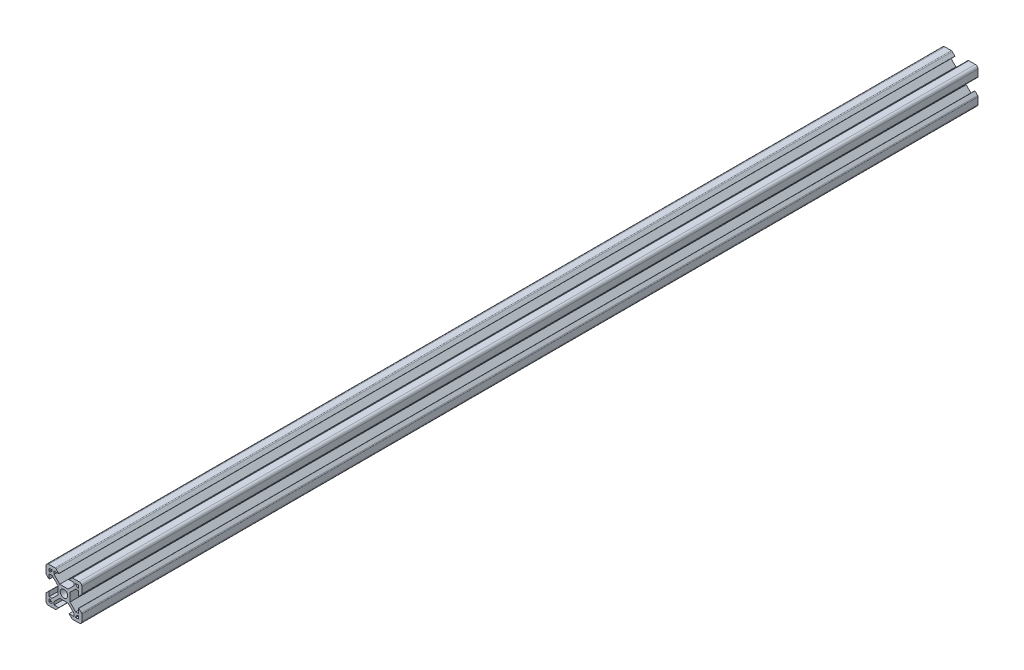
SolidWorks part; units mm, degrees
ref_plane "Front Plane" through (0, 0, 0) normal (0, 0, 1) x (1, 0, 0)
ref_plane "Top Plane" through (0, 0, 0) normal (0, 1, 0) x (1, 0, 0)
ref_plane "Right Plane" through (0, 0, 0) normal (1, 0, 0) x (0, 0, -1)
sketch "Sketch2" plane through (0, 0, 0) normal (0, 0, 1) x (1, 0, 0)
  line L0 (-8.2, 2.89) -> (-8.2, 5.5)
  line L1 (-2.1, 0) -> (-10, 0) construction
  line L2 (0, 2.1) -> (0, 10) construction
  line L3 (-4.9072, 10) -> (-8.5, 10)
  line L4 (-10, 4.9072) -> (-10, 8.5)
  line L5 (-2.1, 0) -> (-3.4, 0) construction
  line L6 (0, 2.1) -> (0, 3.4) construction
  line L7 (0, 3.4) -> (-2.3393, 3.4)
  line L8 (-3.4, 0) -> (-3.4, 2.3393)
  line L9 (-2.89, 8.2) -> (-5.5, 8.2)
  line L10 (-6.57, 8.2) -> (-6.57, 7.66)
  line L11 (-8.2, 6.57) -> (-7.66, 6.57)
  line L12 (-5.5, 8.2) -> (-5.5, 6.5607)
  line L13 (-6.5607, 5.5) -> (-8.2, 5.5)
  line L14 (-8.2, 8.2) -> (-1.4849, 1.4849) construction
  line L15 (-6.5607, 5.5) -> (-3.4, 2.3393)
  line L16 (-5.5, 6.5607) -> (-2.3393, 3.4)
  line L17 (-7.66, 6.57) -> (-6.57, 7.66)
  line L18 (-8.7303, 7.6697) -> (-0.5303, -0.5303) construction
  line L19 (-7.6697, 8.7303) -> (0.5303, 0.5303) construction
  line L20 (-8.2, 8.2) -> (0, 0) construction
  line L21 (-8.2, 6.57) -> (-8.2, 8.2)
  line L22 (-8.2, 0) -> (-8.2, 8.2) construction
  line L23 (-6.57, 8.2) -> (-8.2, 8.2)
  line L24 (0, 8.2) -> (-8.2, 8.2) construction
  line L25 (-10, 0) -> (-10, 10) construction
  line L26 (0, 10) -> (-10, 10) construction
  line L27 (-2.89, 8.31) -> (-2.89, 8.2)
  line L29 (-8.31, 2.89) -> (-8.2, 2.89)
  line L30 (-4.3486, 9.7686) -> (-2.89, 8.31)
  line L31 (-8.31, 2.89) -> (-9.7686, 4.3486)
  arc A0 (0, 2.1) -> (-2.1, 0) centre (0, 0) ccw
  arc A1 (-10, 8.5) -> (-8.5, 10) centre (-8.5, 8.5) cw
  arc A2 (-9.7686, 4.3486) -> (-10, 4.9072) centre (-9.21, 4.9072) cw
  arc A3 (-4.3486, 9.7686) -> (-4.9072, 10) centre (-4.9072, 9.21) ccw
  point P29 (-10, 10)
  point P39 (-10, 4.58)
  point P42 (-4.58, 10)
  dimension "D3" = 2.1
  dimension "D15" = 1.5
  dimension "D22" = 0.79
  dimension "D1" = 10
  dimension "D2" = 10
  dimension "D4" = 1.8
  dimension "D5" = 3.43
  dimension "D6" = 3.43
  dimension "D7" = 0.54
  dimension "D8" = 0.54
  dimension "D9" = 1.07
  dimension "D10" = 1.07
  dimension "D11" = 3.4
  dimension "D12" = 3.4
  dimension "D16" = 7.11
  dimension "D17" = 0.11
  dimension "D18" = 1.69
  dimension "D19" = 0.11
  dimension "D20" = 7.11
  dimension "D21" = 1.69
  dimension "D13" = 0.75
  dimension "D14" = 0.75
sketch "Sketch6" plane through (0, 0, 0) normal (0, 0, 1) x (1, 0, 0)
  line L0 (-3.4, 0) -> (-3.4, 2.3393) construction
  line L1 (-6.5607, 5.5) -> (-3.4, 2.3393) construction
  line L2 (-6.5607, 5.5) -> (-8.2, 5.5) construction
  line L3 (-8.2, 2.89) -> (-8.2, 5.5) construction
  line L4 (-8.31, 2.89) -> (-8.2, 2.89) construction
  line L5 (-7.66, 6.57) -> (-6.57, 7.66)
  line L6 (-6.57, 7.66) -> (-6.57, 8.2)
  line L7 (-6.57, 8.2) -> (-8.2, 8.2)
  line L8 (-8.2, 8.2) -> (-8.2, 6.57)
  line L9 (-8.2, 6.57) -> (-7.66, 6.57)
  line L10 (-7.66, 6.57) -> (-6.57, 7.66)
  line L11 (-6.57, 7.66) -> (-6.57, 8.2)
  line L12 (-6.57, 8.2) -> (-8.2, 8.2)
  line L13 (-8.2, 8.2) -> (-8.2, 6.57)
  line L14 (-8.2, 6.57) -> (-7.66, 6.57)
  line L15 (-8.31, 2.89) -> (-9.7686, 4.3486) construction
  line L16 (-10, 4.9072) -> (-10, 8.5) construction
  line L17 (-4.9072, 10) -> (-8.5, 10) construction
  line L18 (-4.3486, 9.7686) -> (-2.89, 8.31) construction
  line L19 (-2.89, 8.31) -> (-2.89, 8.2) construction
  line L20 (-2.89, 8.2) -> (-5.5, 8.2) construction
  line L21 (-5.5, 8.2) -> (-5.5, 6.5607) construction
  line L22 (-5.5, 6.5607) -> (-2.3393, 3.4) construction
  line L23 (0, 3.4) -> (-2.3393, 3.4) construction
  line L24 (-3.4, -2.3393) -> (-3.4, 2.3393)
  line L25 (-6.5607, 5.5) -> (-3.4, 2.3393)
  line L26 (-6.5607, 5.5) -> (-8.2, 5.5)
  line L27 (-8.2, 2.89) -> (-8.2, 5.5)
  line L28 (-8.31, 2.89) -> (-8.2, 2.89)
  line L29 (-8.31, 2.89) -> (-9.7686, 4.3486)
  line L30 (-10, 4.9072) -> (-10, 8.5)
  line L31 (-4.9072, 10) -> (-8.5, 10)
  line L32 (-4.3486, 9.7686) -> (-2.89, 8.31)
  line L33 (-2.89, 8.31) -> (-2.89, 8.2)
  line L34 (-2.89, 8.2) -> (-5.5, 8.2)
  line L35 (-5.5, 8.2) -> (-5.5, 6.5607)
  line L36 (-5.5, 6.5607) -> (-2.3393, 3.4)
  line L37 (2.3393, 3.4) -> (-2.3393, 3.4)
  line L38 (0, 2.1) -> (0, 10) construction
  line L39 (-2.1, 0) -> (-10, 0) construction
  line L40 (0, 2.1) -> (0, 10) construction
  line L41 (-2.1, 0) -> (-10, 0) construction
  line L42 (2.1, 0) -> (10, 0) construction
  line L43 (5.5, 6.5607) -> (2.3393, 3.4)
  line L44 (5.5, 8.2) -> (5.5, 6.5607)
  line L45 (2.89, 8.2) -> (5.5, 8.2)
  line L46 (2.89, 8.31) -> (2.89, 8.2)
  line L47 (4.3486, 9.7686) -> (2.89, 8.31)
  line L48 (4.9072, 10) -> (8.5, 10)
  line L49 (10, 4.9072) -> (10, 8.5)
  line L50 (8.31, 2.89) -> (9.7686, 4.3486)
  line L51 (8.31, 2.89) -> (8.2, 2.89)
  line L52 (8.2, 2.89) -> (8.2, 5.5)
  line L53 (6.5607, 5.5) -> (8.2, 5.5)
  line L54 (6.5607, 5.5) -> (3.4, 2.3393)
  line L55 (3.4, -2.3393) -> (3.4, 2.3393)
  line L56 (8.2, 6.57) -> (7.66, 6.57)
  line L57 (8.2, 8.2) -> (8.2, 6.57)
  line L58 (6.57, 8.2) -> (8.2, 8.2)
  line L59 (6.57, 7.66) -> (6.57, 8.2)
  line L60 (7.66, 6.57) -> (6.57, 7.66)
  line L61 (0, -2.1) -> (0, -10) construction
  line L62 (7.66, -6.57) -> (6.57, -7.66)
  line L63 (6.57, -7.66) -> (6.57, -8.2)
  line L64 (6.57, -8.2) -> (8.2, -8.2)
  line L65 (8.2, -8.2) -> (8.2, -6.57)
  line L66 (8.2, -6.57) -> (7.66, -6.57)
  line L67 (6.5607, -5.5) -> (3.4, -2.3393)
  line L68 (6.5607, -5.5) -> (8.2, -5.5)
  line L69 (8.2, -2.89) -> (8.2, -5.5)
  line L70 (8.31, -2.89) -> (8.2, -2.89)
  line L71 (8.31, -2.89) -> (9.7686, -4.3486)
  line L72 (10, -4.9072) -> (10, -8.5)
  line L73 (4.9072, -10) -> (8.5, -10)
  line L74 (4.3486, -9.7686) -> (2.89, -8.31)
  line L75 (2.89, -8.31) -> (2.89, -8.2)
  line L76 (2.89, -8.2) -> (5.5, -8.2)
  line L77 (5.5, -8.2) -> (5.5, -6.5607)
  line L78 (5.5, -6.5607) -> (2.3393, -3.4)
  line L79 (2.3393, -3.4) -> (-2.3393, -3.4)
  line L80 (-5.5, -6.5607) -> (-2.3393, -3.4)
  line L81 (-5.5, -8.2) -> (-5.5, -6.5607)
  line L82 (-2.89, -8.2) -> (-5.5, -8.2)
  line L83 (-2.89, -8.31) -> (-2.89, -8.2)
  line L84 (-4.3486, -9.7686) -> (-2.89, -8.31)
  line L85 (-4.9072, -10) -> (-8.5, -10)
  line L86 (-10, -4.9072) -> (-10, -8.5)
  line L87 (-8.31, -2.89) -> (-9.7686, -4.3486)
  line L88 (-8.31, -2.89) -> (-8.2, -2.89)
  line L89 (-8.2, -2.89) -> (-8.2, -5.5)
  line L90 (-6.5607, -5.5) -> (-8.2, -5.5)
  line L91 (-6.5607, -5.5) -> (-3.4, -2.3393)
  line L92 (-8.2, -6.57) -> (-7.66, -6.57)
  line L93 (-8.2, -8.2) -> (-8.2, -6.57)
  line L94 (-6.57, -8.2) -> (-8.2, -8.2)
  line L95 (-6.57, -7.66) -> (-6.57, -8.2)
  line L96 (-7.66, -6.57) -> (-6.57, -7.66)
  arc A0 (0, 2.1) -> (-2.1, 0) centre (0, 0) ccw construction
  arc A1 (-10, 4.9072) -> (-9.7686, 4.3486) centre (-9.21, 4.9072) ccw construction
  arc A2 (-8.5, 10) -> (-10, 8.5) centre (-8.5, 8.5) ccw construction
  arc A3 (-4.3486, 9.7686) -> (-4.9072, 10) centre (-4.9072, 9.21) ccw construction
  circle A4 centre (0, 0) radius 2.1
  arc A5 (-10, 4.9072) -> (-9.7686, 4.3486) centre (-9.21, 4.9072) ccw
  arc A6 (-8.5, 10) -> (-10, 8.5) centre (-8.5, 8.5) ccw
  arc A7 (-4.3486, 9.7686) -> (-4.9072, 10) centre (-4.9072, 9.21) ccw
  arc A8 (4.3486, 9.7686) -> (4.9072, 10) centre (4.9072, 9.21) cw
  arc A9 (8.5, 10) -> (10, 8.5) centre (8.5, 8.5) cw
  arc A10 (10, 4.9072) -> (9.7686, 4.3486) centre (9.21, 4.9072) cw
  arc A11 (10, -4.9072) -> (9.7686, -4.3486) centre (9.21, -4.9072) ccw
  arc A12 (8.5, -10) -> (10, -8.5) centre (8.5, -8.5) ccw
  arc A13 (4.3486, -9.7686) -> (4.9072, -10) centre (4.9072, -9.21) ccw
  arc A14 (-4.3486, -9.7686) -> (-4.9072, -10) centre (-4.9072, -9.21) cw
  arc A15 (-8.5, -10) -> (-10, -8.5) centre (-8.5, -8.5) cw
  arc A16 (-10, -4.9072) -> (-9.7686, -4.3486) centre (-9.21, -4.9072) cw
  point P85 (3.4, 0)
  dimension "D1" = 0
extrude "Boss-Extrude1" add sketch "Sketch6" against normal blind 500
